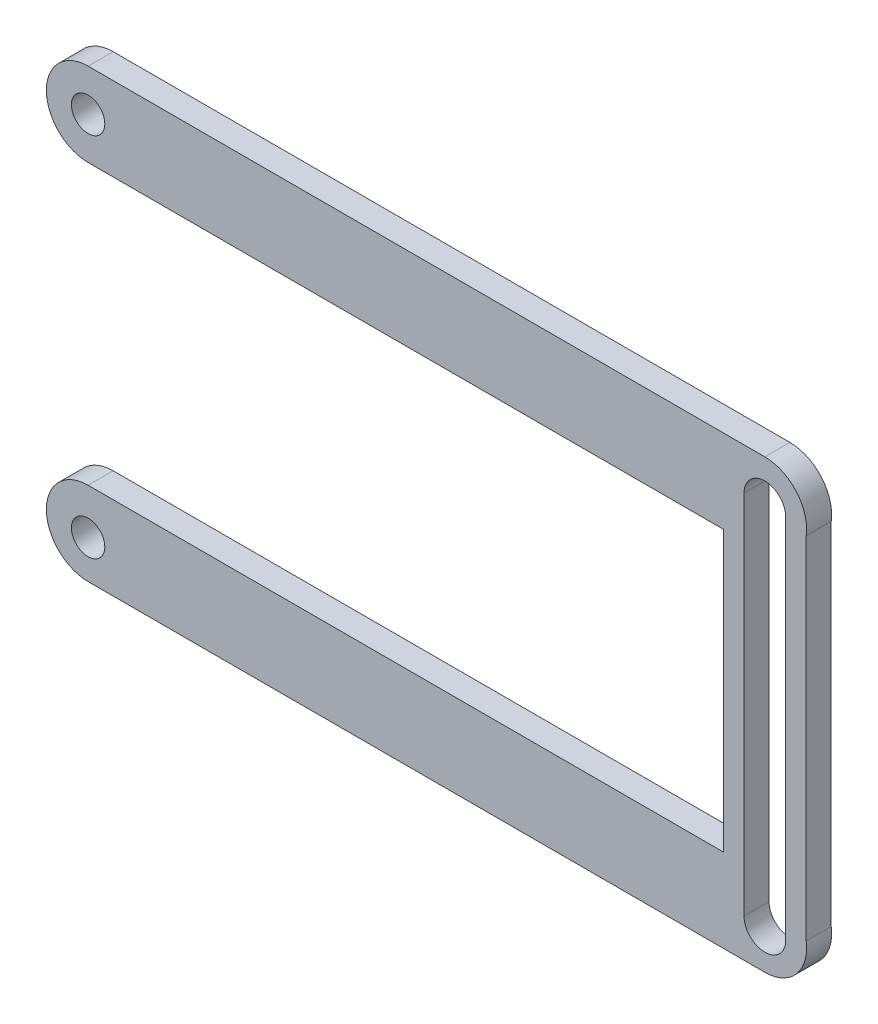
SolidWorks part; units mm, degrees
ref_plane "前视基准面" through (0, 0, 0) normal (0, 0, 1) x (1, 0, 0)
ref_plane "上视基准面" through (0, 0, 0) normal (0, 1, 0) x (1, 0, 0)
ref_plane "右视基准面" through (0, 0, 0) normal (1, 0, 0) x (0, 0, -1)
other "Configuration Table"
sketch "草图1" plane through (0, 0, 0) normal (0, 0, 1) x (1, 0, 0)
  line L0 (-50.3364, 19.9101) -> (30.7502, 19.9101) construction
  line L1 (-50.3364, 24.9101) -> (30.7502, 24.9101)
  line L2 (-50.3364, 14.9101) -> (30.7502, 14.9101)
  line L3 (-50.3364, -23.5751) -> (30.7502, -23.5751) construction
  line L4 (-50.3364, -18.5751) -> (30.7502, -18.5751)
  line L5 (-50.3364, -28.5751) -> (30.7502, -28.5751)
  line L6 (-50.3364, 19.9101) -> (-50.3364, -23.5751) construction
  line L7 (30.7502, 19.9101) -> (30.7502, -23.5751) construction
  line L8 (35.6984, 19.9101) -> (35.6984, -23.5751)
  line L9 (25.8021, 19.9101) -> (25.8021, -23.5751)
  line L10 (30.7502, -23.5751) -> (30.7502, 19.9101) construction
  line L13 (28.2502, -23.5751) -> (28.2502, 19.9101)
  line L14 (33.2502, -23.5751) -> (33.2502, 19.9101)
  arc A0 (-50.3364, 24.9101) -> (-50.3364, 14.9101) centre (-50.3364, 19.9101) ccw
  arc A1 (30.7502, 14.9101) -> (30.7502, 24.9101) centre (30.7502, 19.9101) ccw
  arc A2 (-50.3364, -18.5751) -> (-50.3364, -28.5751) centre (-50.3364, -23.5751) ccw
  arc A3 (30.7502, -28.5751) -> (30.7502, -18.5751) centre (30.7502, -23.5751) ccw
  arc A4 (35.6984, 19.9101) -> (25.8021, 19.9101) centre (30.7502, 19.9101) ccw
  arc A5 (25.8021, -23.5751) -> (35.6984, -23.5751) centre (30.7502, -23.5751) ccw
  circle A6 centre (-50.3364, 19.9101) radius 2
  circle A7 centre (-50.3364, -23.5751) radius 2
  arc A10 (28.2502, -23.5751) -> (33.2502, -23.5751) centre (30.7502, -23.5751) ccw
  arc A11 (33.2502, 19.9101) -> (28.2502, 19.9101) centre (30.7502, 19.9101) ccw
  point P2 (-9.7931, 19.9101)
  point P7 (-9.7931, -23.5751)
  point P18 (30.7502, -1.8325)
  point P27 (30.7502, -1.8325)
extrude "凸台-拉伸1" add sketch "草图1" against normal blind 3 contours A4 L8 A1 L1 A0 L2 L9 A6 | L5 A3 L4 A2
sketch "草图6" plane through (0, 0, 0) normal (0, 0, 1) x (1, 0, 0)
  line L0 (-50.3364, -23.9915) -> (-50.3364, 19.9101) construction
  circle A0 centre (-50.3364, -23.9915) radius 2
  point P2 (0, 0)
  point P5 (0, 0)
  point P6 (0, 0)
sketch "草图10" plane through (0, 0, 0) normal (0, 0, 1) x (1, 0, 0)
extrude "切除-拉伸1" cut sketch "草图6" against normal blind 6 contours A0
sketch "草图13" plane through (0, 0, 0) normal (0, 0, 1) x (1, 0, 0)
  line L0 (30.7502, 19.9101) -> (30.7502, -23.9915) construction
  line L1 (33.2484, 19.9101) -> (33.2484, -23.9915)
  line L2 (28.2521, 19.9101) -> (28.2521, -23.9915)
  line L3 (35.6984, 19.1921) -> (35.6984, -22.8571) construction
  line L4 (25.8021, 14.9101) -> (25.8021, -18.5751) construction
  line L5 (-50.3364, -23.9915) -> (30.7502, -23.9915) construction
  line L6 (30.7502, -23.9915) -> (-50.3364, -23.9915) construction
  line L7 (-50.3364, 19.9101) -> (30.7502, 19.9101) construction
  line L8 (-50.3364, 24.9101) -> (30.7502, 24.9101) construction
  line L9 (-50.3364, -28.5751) -> (30.7502, -28.5751) construction
  arc A0 (33.2484, 19.9101) -> (28.2521, 19.9101) centre (30.7502, 19.9101) ccw
  arc A1 (28.2521, -23.9915) -> (33.2484, -23.9915) centre (30.7502, -23.9915) ccw
  point P2 (30.7502, -2.0407)
  dimension "D1" = 2.45
  dimension "D2" = 2.45
  dimension "D3" = 9.8964
extrude "切除-拉伸2" cut sketch "草图13" against normal blind 6 contours L2 A1 L1 A0
